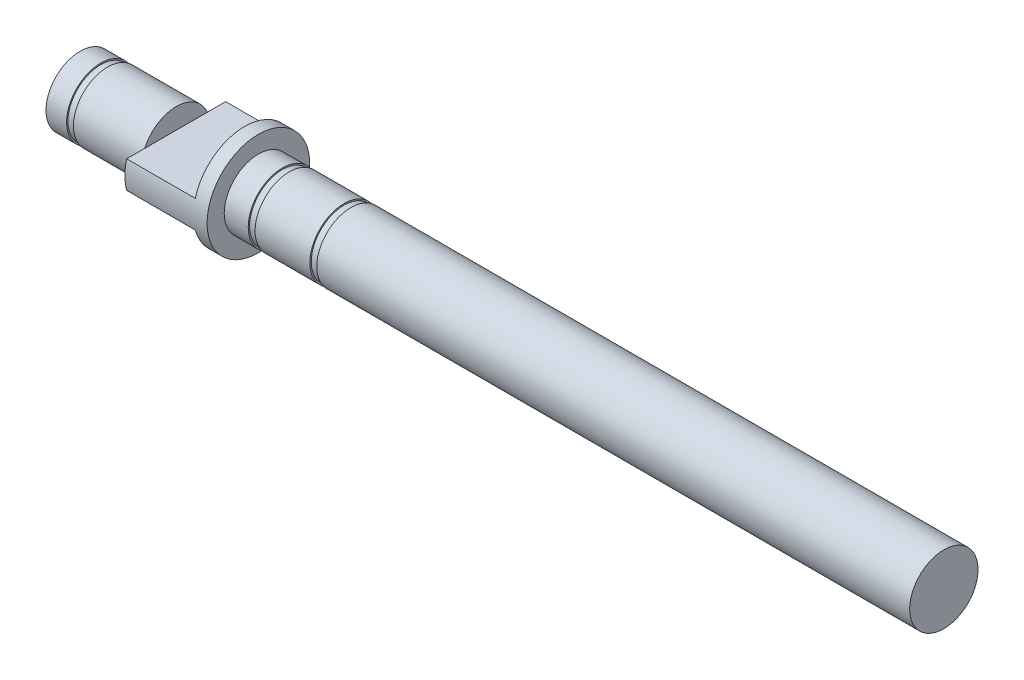
SolidWorks part; units mm, degrees
material "ASTM A36 Steel"
ref_plane "Front Plane" through (0, 0, 0) normal (0, 0, 1) x (1, 0, 0)
ref_plane "Top Plane" through (0, 0, 0) normal (0, 1, 0) x (1, 0, 0)
ref_plane "Right Plane" through (0, 0, 0) normal (1, 0, 0) x (0, 0, -1)
sketch "Sketch3" plane through (0, 0, 0) normal (0, 1, 0) x (1, 0, 0)
  line L0 (0, 0) -> (41.8214, 0) construction
  line L1 (0, 0) -> (126, 0)
  line L2 (126, 0) -> (126, 4.99)
  line L3 (126, 4.99) -> (39.5, 4.99)
  line L4 (39.5, 4.99) -> (39.5, 4.79)
  line L5 (39.5, 4.79) -> (38.5, 4.79)
  line L6 (38.5, 4.79) -> (38.5, 4.99)
  line L7 (38.5, 4.99) -> (30.5, 4.99)
  line L8 (30.5, 4.99) -> (30.5, 4.79)
  line L9 (30.5, 4.79) -> (29.5, 4.79)
  line L10 (29.5, 4.79) -> (29.5, 4.99)
  line L11 (29.5, 4.99) -> (26, 4.99)
  line L12 (26, 4.99) -> (26, 7.49)
  line L13 (26, 7.49) -> (14, 7.49)
  line L14 (14, 7.49) -> (14, 4.99)
  line L15 (14, 4.99) -> (4, 4.99)
  line L16 (4, 4.99) -> (4, 4.79)
  line L17 (4, 4.79) -> (3, 4.79)
  line L18 (3, 4.79) -> (3, 4.99)
  line L19 (3, 4.99) -> (0, 4.99)
  line L20 (0, 4.99) -> (0, 0)
  dimension "D1" = 4.99
  dimension "D2" = 0.2
  dimension "D3" = 1
  dimension "D4" = 3
  dimension "D5" = 10
  dimension "D6" = 12
  dimension "D7" = 3.5
  dimension "D8" = 8
  dimension "D9" = 100
  dimension "D10" = 2.5
revolve "Revolve1" add sketch "Sketch3" angle 360 about L0
sketch "Sketch10" plane through (14, 0, 0) normal (-1, 0, 0) x (0, 0, 1)
  line L0 (7.2284, 2) -> (-7.2284, 2)
  line L2 (7.2284, -2) -> (-7.2284, -2)
  arc A1 (-7.2284, 2) -> (7.2284, 2) centre (0, 0) cw
  arc A2 (-7.2284, -2) -> (7.2284, -2) centre (0, 0) ccw
  point P2 (0, 7.5)
  point P4 (0, -7.5)
  dimension "D1" = 4
  dimension "D3" = 7.5
  dimension "D4" = 7.5
extrude "Cut-Extrude8" cut sketch "Sketch10" against normal blind 10
